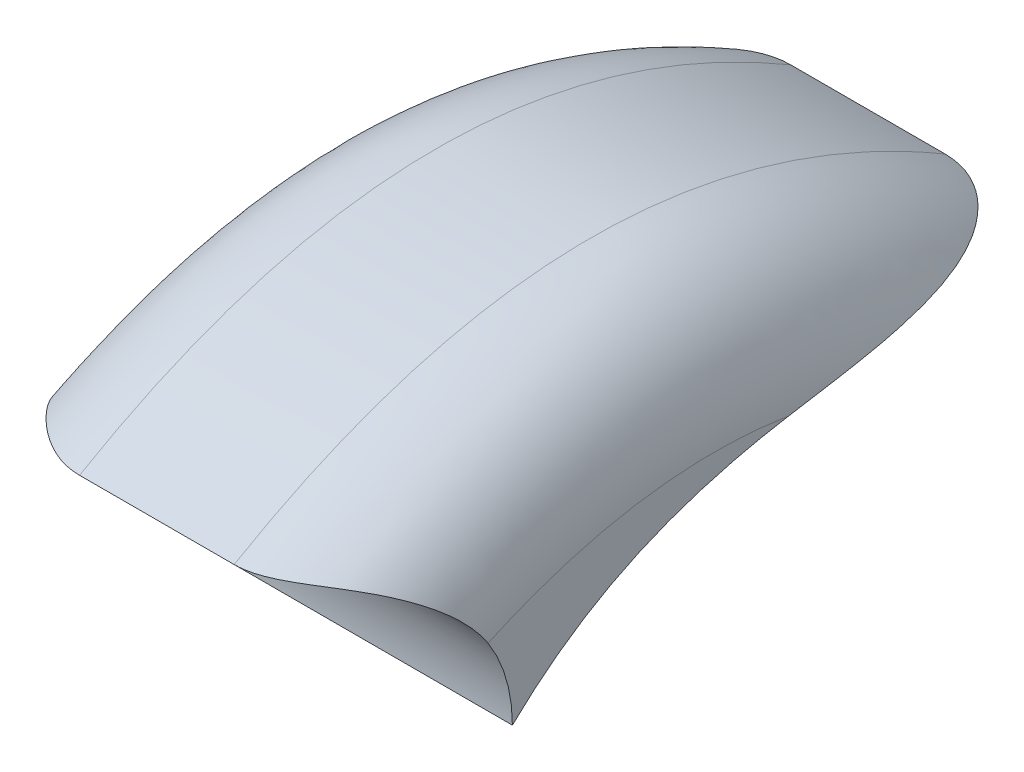
SolidWorks part; units mm, degrees
ref_plane "Front Plane" through (0, 0, 0) normal (0, 0, 1) x (1, 0, 0)
ref_plane "Top Plane" through (0, 0, 0) normal (0, 1, 0) x (1, 0, 0)
ref_plane "Right Plane" through (0, 0, 0) normal (1, 0, 0) x (0, 0, -1)
sketch "Sketch2" plane through (0, 0, 0) normal (1, 0, 0) x (0, 0, -1)
  arc A0 (12.7, 0) -> (0, 12.7) centre (0, 0) ccw
  spline S0 degree 2 poles (0, 12.7) (29.2899, 29.8926) (58.42, 12.7) knots 0 0 0 1 1 1
  spline S1 degree 3 poles (12.7, 0) (25.4775, 12.4415) (42.2764, 11.2212) (58.42, 12.7) knots 0 0 0 0 1 1 1 1
  point P1 (31.1961, 9.8092)
  point P12 (29.7112, 21.2941)
  dimension "D2" = 25.4
extrude "Boss-Extrude1" add sketch "Sketch2" along normal blind 33.02
fillet "Fillet1" radius 10.16 2 edges
shell "Shell1" thickness 5.08
